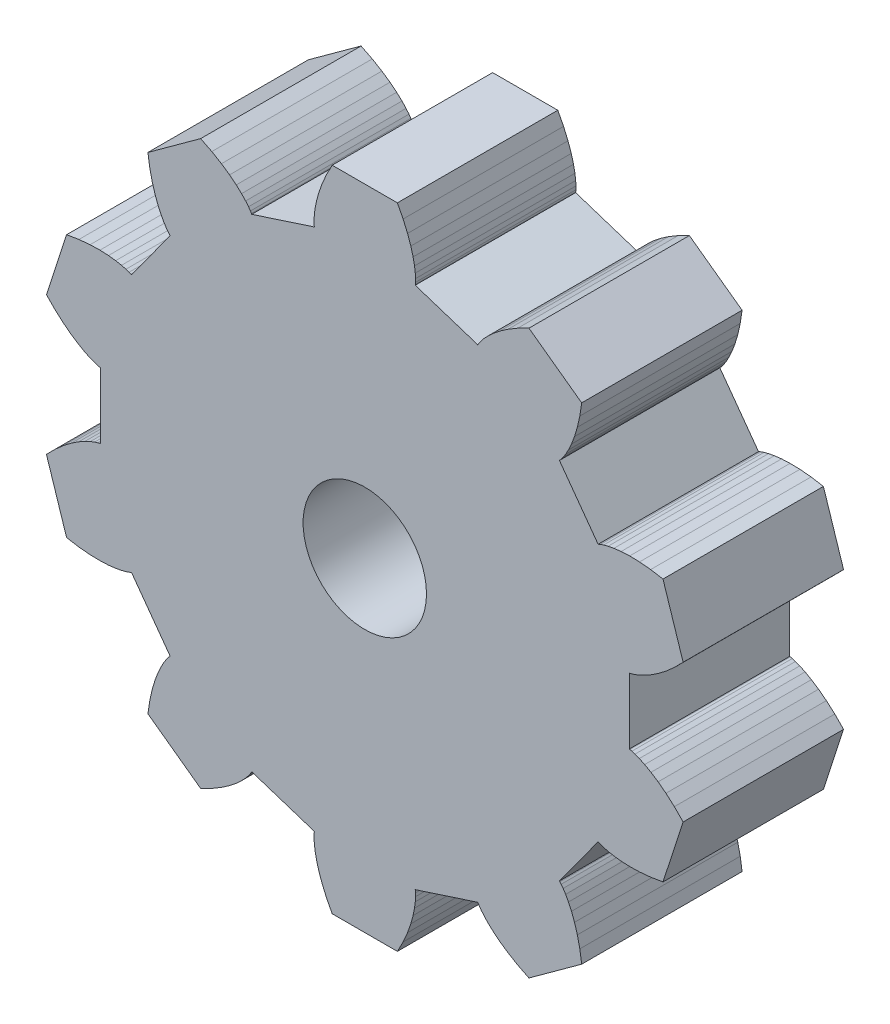
SolidWorks part; units mm, degrees
ref_plane "Front Plane" through (0, 0, 0) normal (0, 0, 1) x (1, 0, 0)
ref_plane "Top Plane" through (0, 0, 0) normal (0, 1, 0) x (1, 0, 0)
ref_plane "Right Plane" through (0, 0, 0) normal (1, 0, 0) x (0, 0, -1)
sketch "Model" plane through (0, 0, 0) normal (0, 0, 1) x (1, 0, 0)
  line L0 (10.7174, -1.3335) -> (10.7174, 1.3335)
  line L1 (10.7174, 1.3335) -> (10.7436, 1.338)
  line L2 (10.7436, 1.338) -> (10.8215, 1.3565)
  line L3 (10.8215, 1.3565) -> (10.9487, 1.3961)
  line L4 (10.9487, 1.3961) -> (11.1226, 1.4638)
  line L5 (11.1226, 1.4638) -> (11.3396, 1.5663)
  line L6 (11.3396, 1.5663) -> (11.5954, 1.7098)
  line L7 (11.5954, 1.7098) -> (11.885, 1.9002)
  line L8 (11.885, 1.9002) -> (12.203, 2.1427)
  line L9 (12.203, 2.1427) -> (12.5432, 2.4422)
  line L10 (12.5432, 2.4422) -> (12.899, 2.8027)
  line L11 (9.4543, 5.2207) -> (9.4782, 5.2325)
  line L12 (9.4782, 5.2325) -> (9.5521, 5.2633)
  line L13 (9.5521, 5.2633) -> (9.6783, 5.3061)
  line L14 (9.6783, 5.3061) -> (9.8588, 5.3535)
  line L15 (9.8588, 5.3535) -> (10.0946, 5.3981)
  line L16 (10.0946, 5.3981) -> (10.3859, 5.4323)
  line L17 (10.3859, 5.4323) -> (10.7321, 5.4485)
  line L18 (10.7321, 5.4485) -> (11.1319, 5.4392)
  line L19 (11.1319, 5.4392) -> (11.5831, 5.3969)
  line L20 (11.5831, 5.3969) -> (12.0829, 5.3144)
  line L21 (12.899, 2.8027) -> (12.0829, 5.3144)
  line L22 (9.4543, 5.2207) -> (7.8867, 7.3783)
  line L23 (7.8867, 7.3783) -> (7.9053, 7.3974)
  line L24 (7.9053, 7.3974) -> (7.9574, 7.4581)
  line L25 (7.9574, 7.4581) -> (8.0371, 7.565)
  line L26 (8.0371, 7.565) -> (8.138, 7.722)
  line L27 (8.138, 7.722) -> (8.2533, 7.9324)
  line L28 (8.2533, 7.9324) -> (8.3758, 8.1989)
  line L29 (8.3758, 8.1989) -> (8.4983, 8.5231)
  line L30 (8.4983, 8.5231) -> (8.613, 8.9062)
  line L31 (8.613, 8.9062) -> (8.7122, 9.3485)
  line L32 (8.7122, 9.3485) -> (8.7881, 9.8493)
  line L33 (4.58, 9.7808) -> (4.5925, 9.8043)
  line L34 (4.5925, 9.8043) -> (4.6341, 9.8727)
  line L35 (4.6341, 9.8727) -> (4.7111, 9.9815)
  line L36 (4.7111, 9.9815) -> (4.8293, 10.1259)
  line L37 (4.8293, 10.1259) -> (4.9938, 10.3006)
  line L38 (4.9938, 10.3006) -> (5.2093, 10.4995)
  line L39 (5.2093, 10.4995) -> (5.4799, 10.7161)
  line L40 (5.4799, 10.7161) -> (5.8088, 10.9436)
  line L41 (5.8088, 10.9436) -> (6.1987, 11.1746)
  line L42 (6.1987, 11.1746) -> (6.6516, 11.4016)
  line L43 (8.7881, 9.8493) -> (6.6516, 11.4016)
  line L44 (4.58, 9.7808) -> (2.0437, 10.6049)
  line L45 (2.0437, 10.6049) -> (2.0475, 10.6313)
  line L46 (2.0475, 10.6313) -> (2.0539, 10.711)
  line L47 (2.0539, 10.711) -> (2.0556, 10.8443)
  line L48 (2.0556, 10.8443) -> (2.0449, 11.0306)
  line L49 (2.0449, 11.0306) -> (2.0145, 11.2686)
  line L50 (2.0145, 11.2686) -> (1.957, 11.5562)
  line L51 (1.957, 11.5562) -> (1.8655, 11.8905)
  line L52 (1.8655, 11.8905) -> (1.7331, 12.2679)
  line L53 (1.7331, 12.2679) -> (1.5534, 12.684)
  line L54 (1.5534, 12.684) -> (1.3204, 13.1338)
  line L55 (-2.0437, 10.6049) -> (-2.0475, 10.6313)
  line L56 (-2.0475, 10.6313) -> (-2.0539, 10.711)
  line L57 (-2.0539, 10.711) -> (-2.0556, 10.8443)
  line L58 (-2.0556, 10.8443) -> (-2.0449, 11.0306)
  line L59 (-2.0449, 11.0306) -> (-2.0145, 11.2686)
  line L60 (-2.0145, 11.2686) -> (-1.957, 11.5562)
  line L61 (-1.957, 11.5562) -> (-1.8655, 11.8905)
  line L62 (-1.8655, 11.8905) -> (-1.7331, 12.2679)
  line L63 (-1.7331, 12.2679) -> (-1.5534, 12.684)
  line L64 (-1.5534, 12.684) -> (-1.3204, 13.1338)
  line L65 (1.3204, 13.1338) -> (-1.3204, 13.1338)
  line L66 (-2.0437, 10.6049) -> (-4.58, 9.7808)
  line L67 (-4.58, 9.7808) -> (-4.5925, 9.8043)
  line L68 (-4.5925, 9.8043) -> (-4.6341, 9.8727)
  line L69 (-4.6341, 9.8727) -> (-4.7111, 9.9815)
  line L70 (-4.7111, 9.9815) -> (-4.8293, 10.1259)
  line L71 (-4.8293, 10.1259) -> (-4.9938, 10.3006)
  line L72 (-4.9938, 10.3006) -> (-5.2093, 10.4995)
  line L73 (-5.2093, 10.4995) -> (-5.4799, 10.7161)
  line L74 (-5.4799, 10.7161) -> (-5.8088, 10.9436)
  line L75 (-5.8088, 10.9436) -> (-6.1987, 11.1746)
  line L76 (-6.1987, 11.1746) -> (-6.6516, 11.4016)
  line L77 (-7.8867, 7.3783) -> (-7.9053, 7.3974)
  line L78 (-7.9053, 7.3974) -> (-7.9574, 7.4581)
  line L79 (-7.9574, 7.4581) -> (-8.0371, 7.565)
  line L80 (-8.0371, 7.565) -> (-8.138, 7.722)
  line L81 (-8.138, 7.722) -> (-8.2533, 7.9324)
  line L82 (-8.2533, 7.9324) -> (-8.3758, 8.1989)
  line L83 (-8.3758, 8.1989) -> (-8.4983, 8.5231)
  line L84 (-8.4983, 8.5231) -> (-8.613, 8.9062)
  line L85 (-8.613, 8.9062) -> (-8.7122, 9.3485)
  line L86 (-8.7122, 9.3485) -> (-8.7881, 9.8493)
  line L87 (-6.6516, 11.4016) -> (-8.7881, 9.8493)
  line L88 (-7.8867, 7.3783) -> (-9.4543, 5.2207)
  line L89 (-9.4543, 5.2207) -> (-9.4782, 5.2325)
  line L90 (-9.4782, 5.2325) -> (-9.5521, 5.2633)
  line L91 (-9.5521, 5.2633) -> (-9.6783, 5.3061)
  line L92 (-9.6783, 5.3061) -> (-9.8588, 5.3535)
  line L93 (-9.8588, 5.3535) -> (-10.0946, 5.3981)
  line L94 (-10.0946, 5.3981) -> (-10.3859, 5.4323)
  line L95 (-10.3859, 5.4323) -> (-10.7321, 5.4485)
  line L96 (-10.7321, 5.4485) -> (-11.1319, 5.4392)
  line L97 (-11.1319, 5.4392) -> (-11.5831, 5.3969)
  line L98 (-11.5831, 5.3969) -> (-12.0829, 5.3144)
  line L99 (-10.7174, 1.3335) -> (-10.7436, 1.338)
  line L100 (-10.7436, 1.338) -> (-10.8215, 1.3565)
  line L101 (-10.8215, 1.3565) -> (-10.9487, 1.3961)
  line L102 (-10.9487, 1.3961) -> (-11.1226, 1.4638)
  line L103 (-11.1226, 1.4638) -> (-11.3396, 1.5663)
  line L104 (-11.3396, 1.5663) -> (-11.5954, 1.7098)
  line L105 (-11.5954, 1.7098) -> (-11.885, 1.9002)
  line L106 (-11.885, 1.9002) -> (-12.203, 2.1427)
  line L107 (-12.203, 2.1427) -> (-12.5432, 2.4422)
  line L108 (-12.5432, 2.4422) -> (-12.899, 2.8027)
  line L109 (-12.0829, 5.3144) -> (-12.899, 2.8027)
  line L110 (-10.7174, 1.3335) -> (-10.7174, -1.3335)
  line L111 (-10.7174, -1.3335) -> (-10.7436, -1.338)
  line L112 (-10.7436, -1.338) -> (-10.8215, -1.3565)
  line L113 (-10.8215, -1.3565) -> (-10.9487, -1.3961)
  line L114 (-10.9487, -1.3961) -> (-11.1226, -1.4638)
  line L115 (-11.1226, -1.4638) -> (-11.3396, -1.5663)
  line L116 (-11.3396, -1.5663) -> (-11.5954, -1.7098)
  line L117 (-11.5954, -1.7098) -> (-11.885, -1.9002)
  line L118 (-11.885, -1.9002) -> (-12.203, -2.1427)
  line L119 (-12.203, -2.1427) -> (-12.5432, -2.4422)
  line L120 (-12.5432, -2.4422) -> (-12.899, -2.8027)
  line L121 (-9.4543, -5.2207) -> (-9.4782, -5.2325)
  line L122 (-9.4782, -5.2325) -> (-9.5521, -5.2633)
  line L123 (-9.5521, -5.2633) -> (-9.6783, -5.3061)
  line L124 (-9.6783, -5.3061) -> (-9.8588, -5.3535)
  line L125 (-9.8588, -5.3535) -> (-10.0946, -5.3981)
  line L126 (-10.0946, -5.3981) -> (-10.3859, -5.4323)
  line L127 (-10.3859, -5.4323) -> (-10.7321, -5.4485)
  line L128 (-10.7321, -5.4485) -> (-11.1319, -5.4392)
  line L129 (-11.1319, -5.4392) -> (-11.5831, -5.3969)
  line L130 (-11.5831, -5.3969) -> (-12.0829, -5.3144)
  line L131 (-12.899, -2.8027) -> (-12.0829, -5.3144)
  line L132 (-9.4543, -5.2207) -> (-7.8867, -7.3783)
  line L133 (-7.8867, -7.3783) -> (-7.9053, -7.3974)
  line L134 (-7.9053, -7.3974) -> (-7.9574, -7.4581)
  line L135 (-7.9574, -7.4581) -> (-8.0371, -7.565)
  line L136 (-8.0371, -7.565) -> (-8.138, -7.722)
  line L137 (-8.138, -7.722) -> (-8.2533, -7.9324)
  line L138 (-8.2533, -7.9324) -> (-8.3758, -8.1989)
  line L139 (-8.3758, -8.1989) -> (-8.4983, -8.5231)
  line L140 (-8.4983, -8.5231) -> (-8.613, -8.9062)
  line L141 (-8.613, -8.9062) -> (-8.7122, -9.3485)
  line L142 (-8.7122, -9.3485) -> (-8.7881, -9.8493)
  line L143 (-4.58, -9.7808) -> (-4.5925, -9.8043)
  line L144 (-4.5925, -9.8043) -> (-4.6341, -9.8727)
  line L145 (-4.6341, -9.8727) -> (-4.7111, -9.9815)
  line L146 (-4.7111, -9.9815) -> (-4.8293, -10.1259)
  line L147 (-4.8293, -10.1259) -> (-4.9938, -10.3006)
  line L148 (-4.9938, -10.3006) -> (-5.2093, -10.4995)
  line L149 (-5.2093, -10.4995) -> (-5.4799, -10.7161)
  line L150 (-5.4799, -10.7161) -> (-5.8088, -10.9436)
  line L151 (-5.8088, -10.9436) -> (-6.1987, -11.1746)
  line L152 (-6.1987, -11.1746) -> (-6.6516, -11.4016)
  line L153 (-8.7881, -9.8493) -> (-6.6516, -11.4016)
  line L154 (-4.58, -9.7808) -> (-2.0437, -10.6049)
  line L155 (-2.0437, -10.6049) -> (-2.0475, -10.6313)
  line L156 (-2.0475, -10.6313) -> (-2.0539, -10.711)
  line L157 (-2.0539, -10.711) -> (-2.0556, -10.8443)
  line L158 (-2.0556, -10.8443) -> (-2.0449, -11.0306)
  line L159 (-2.0449, -11.0306) -> (-2.0145, -11.2686)
  line L160 (-2.0145, -11.2686) -> (-1.957, -11.5562)
  line L161 (-1.957, -11.5562) -> (-1.8655, -11.8905)
  line L162 (-1.8655, -11.8905) -> (-1.7331, -12.2679)
  line L163 (-1.7331, -12.2679) -> (-1.5534, -12.684)
  line L164 (-1.5534, -12.684) -> (-1.3204, -13.1338)
  line L165 (2.0437, -10.6049) -> (2.0475, -10.6313)
  line L166 (2.0475, -10.6313) -> (2.0539, -10.711)
  line L167 (2.0539, -10.711) -> (2.0556, -10.8443)
  line L168 (2.0556, -10.8443) -> (2.0449, -11.0306)
  line L169 (2.0449, -11.0306) -> (2.0145, -11.2686)
  line L170 (2.0145, -11.2686) -> (1.957, -11.5562)
  line L171 (1.957, -11.5562) -> (1.8655, -11.8905)
  line L172 (1.8655, -11.8905) -> (1.7331, -12.2679)
  line L173 (1.7331, -12.2679) -> (1.5534, -12.684)
  line L174 (1.5534, -12.684) -> (1.3204, -13.1338)
  line L175 (-1.3204, -13.1338) -> (1.3204, -13.1338)
  line L176 (2.0437, -10.6049) -> (4.58, -9.7808)
  line L177 (4.58, -9.7808) -> (4.5925, -9.8043)
  line L178 (4.5925, -9.8043) -> (4.6341, -9.8727)
  line L179 (4.6341, -9.8727) -> (4.7111, -9.9815)
  line L180 (4.7111, -9.9815) -> (4.8293, -10.1259)
  line L181 (4.8293, -10.1259) -> (4.9938, -10.3006)
  line L182 (4.9938, -10.3006) -> (5.2093, -10.4995)
  line L183 (5.2093, -10.4995) -> (5.4799, -10.7161)
  line L184 (5.4799, -10.7161) -> (5.8088, -10.9436)
  line L185 (5.8088, -10.9436) -> (6.1987, -11.1746)
  line L186 (6.1987, -11.1746) -> (6.6516, -11.4016)
  line L187 (7.8867, -7.3783) -> (7.9053, -7.3974)
  line L188 (7.9053, -7.3974) -> (7.9574, -7.4581)
  line L189 (7.9574, -7.4581) -> (8.0371, -7.565)
  line L190 (8.0371, -7.565) -> (8.138, -7.722)
  line L191 (8.138, -7.722) -> (8.2533, -7.9324)
  line L192 (8.2533, -7.9324) -> (8.3758, -8.1989)
  line L193 (8.3758, -8.1989) -> (8.4983, -8.5231)
  line L194 (8.4983, -8.5231) -> (8.613, -8.9062)
  line L195 (8.613, -8.9062) -> (8.7122, -9.3485)
  line L196 (8.7122, -9.3485) -> (8.7881, -9.8493)
  line L197 (6.6516, -11.4016) -> (8.7881, -9.8493)
  line L198 (7.8867, -7.3783) -> (9.4543, -5.2207)
  line L199 (9.4543, -5.2207) -> (9.4782, -5.2325)
  line L200 (9.4782, -5.2325) -> (9.5521, -5.2633)
  line L201 (9.5521, -5.2633) -> (9.6783, -5.3061)
  line L202 (9.6783, -5.3061) -> (9.8588, -5.3535)
  line L203 (9.8588, -5.3535) -> (10.0946, -5.3981)
  line L204 (10.0946, -5.3981) -> (10.3859, -5.4323)
  line L205 (10.3859, -5.4323) -> (10.7321, -5.4485)
  line L206 (10.7321, -5.4485) -> (11.1319, -5.4392)
  line L207 (11.1319, -5.4392) -> (11.5831, -5.3969)
  line L208 (11.5831, -5.3969) -> (12.0829, -5.3144)
  line L209 (10.7174, -1.3335) -> (10.7436, -1.338)
  line L210 (10.7436, -1.338) -> (10.8215, -1.3565)
  line L211 (10.8215, -1.3565) -> (10.9487, -1.3961)
  line L212 (10.9487, -1.3961) -> (11.1226, -1.4638)
  line L213 (11.1226, -1.4638) -> (11.3396, -1.5663)
  line L214 (11.3396, -1.5663) -> (11.5954, -1.7098)
  line L215 (11.5954, -1.7098) -> (11.885, -1.9002)
  line L216 (11.885, -1.9002) -> (12.203, -2.1427)
  line L217 (12.203, -2.1427) -> (12.5432, -2.4422)
  line L218 (12.5432, -2.4422) -> (12.899, -2.8027)
  line L219 (12.0829, -5.3144) -> (12.899, -2.8027)
extrude "Boss-Extrude1" add sketch "Model" along normal blind 6.5
sketch "Sketch1" plane through (0, 0, 6.5) normal (0, 0, 1) x (1, 0, 0)
  circle A0 centre (0, 0) radius 2.5
  dimension "D1" = 5
extrude "Cut-Extrude1" cut sketch "Sketch1" against normal up to next
